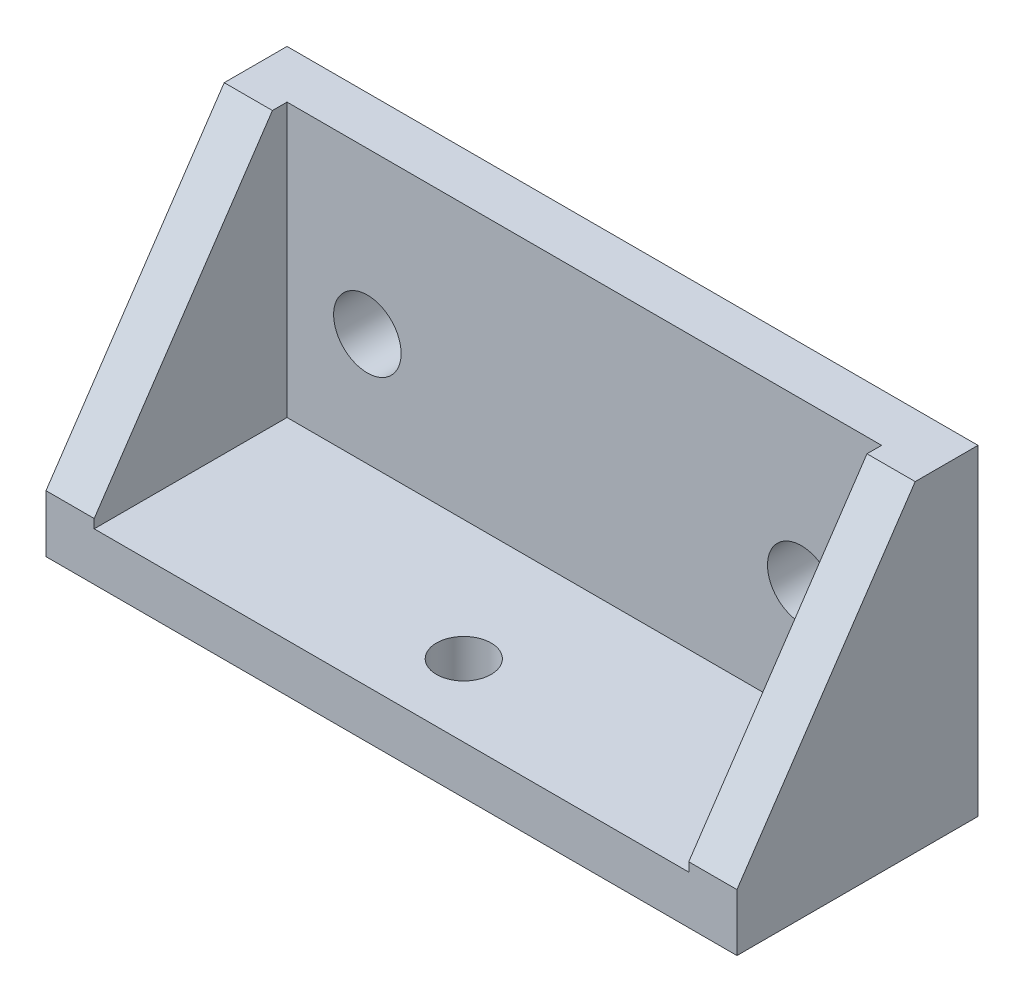
SolidWorks part; units mm, degrees
material "ABS"
ref_plane "Front Plane" through (0, 0, 0) normal (0, 0, 1) x (1, 0, 0)
ref_plane "Top Plane" through (0, 0, 0) normal (0, 1, 0) x (1, 0, 0)
ref_plane "Right Plane" through (0, 0, 0) normal (1, 0, 0) x (0, 0, -1)
sketch "Sketch3" plane through (0, 0, 0) normal (1, 0, 0) x (0, 0, -1)
  line L0 (0, 0) -> (0, 20)
  line L1 (0, 20) -> (-3.9089, 20)
  line L2 (-3.9089, 20) -> (-15, 3.5567)
  line L3 (-15, 3.5567) -> (-15, 0)
  line L4 (-15, 0) -> (0, 0)
  dimension "D1" = 20
  dimension "D2" = 15
  dimension "D3" = 3.5567
  dimension "D4" = 3.9089
extrude "Boss-Extrude3" add sketch "Sketch3" along normal mid plane 43
sketch "Sketch4" plane through (0, 20, 0) normal (0, 1, 0) x (1, 0, 0)
  line L0 (21.5, -15) -> (-21.5, -15) construction
  line L1 (-18.5, -3) -> (18.5, -3)
  line L2 (-18.5, -3) -> (-18.5, -15)
  line L3 (-18.5, -15) -> (18.5, -15)
  line L4 (18.5, -3) -> (18.5, -15)
  line L5 (-21.5, -3.9088) -> (-21.5, -15) construction
  line L6 (21.5, -3.9088) -> (21.5, -15) construction
  line L7 (21.5, 0) -> (-21.5, 0) construction
  dimension "D1" = 3
  dimension "D2" = 3
  dimension "D3" = 3
extrude "Cut-Extrude1" cut sketch "Sketch4" against normal blind 17
sketch "Sketch5" plane through (0, 0, 3) normal (0, 0, 1) x (1, 0, 0)
  line L0 (-13.5, 10) -> (13.5, 10) construction
  line L1 (0, 10) -> (0, 20) construction
  line L2 (18.5, 20) -> (-18.5, 20) construction
  circle A0 centre (-13.5, 10) radius 2.1
  circle A1 centre (13.5, 10) radius 2.1
  dimension "D1" = 27
  dimension "D2" = 4.2
  dimension "D3" = 10
extrude "Cut-Extrude2" cut sketch "Sketch5" against normal through all
sketch "Sketch6" plane through (0, 3, 0) normal (0, 1, 0) x (1, 0, 0)
  line L0 (0, -10.5) -> (0, -15) construction
  line L1 (-18.5, -15) -> (18.5, -15) construction
  circle A0 centre (0, -10.5) radius 1.7
  dimension "D1" = 3.4
  dimension "D2" = 4.5
extrude "Cut-Extrude3" cut sketch "Sketch6" against normal through all
